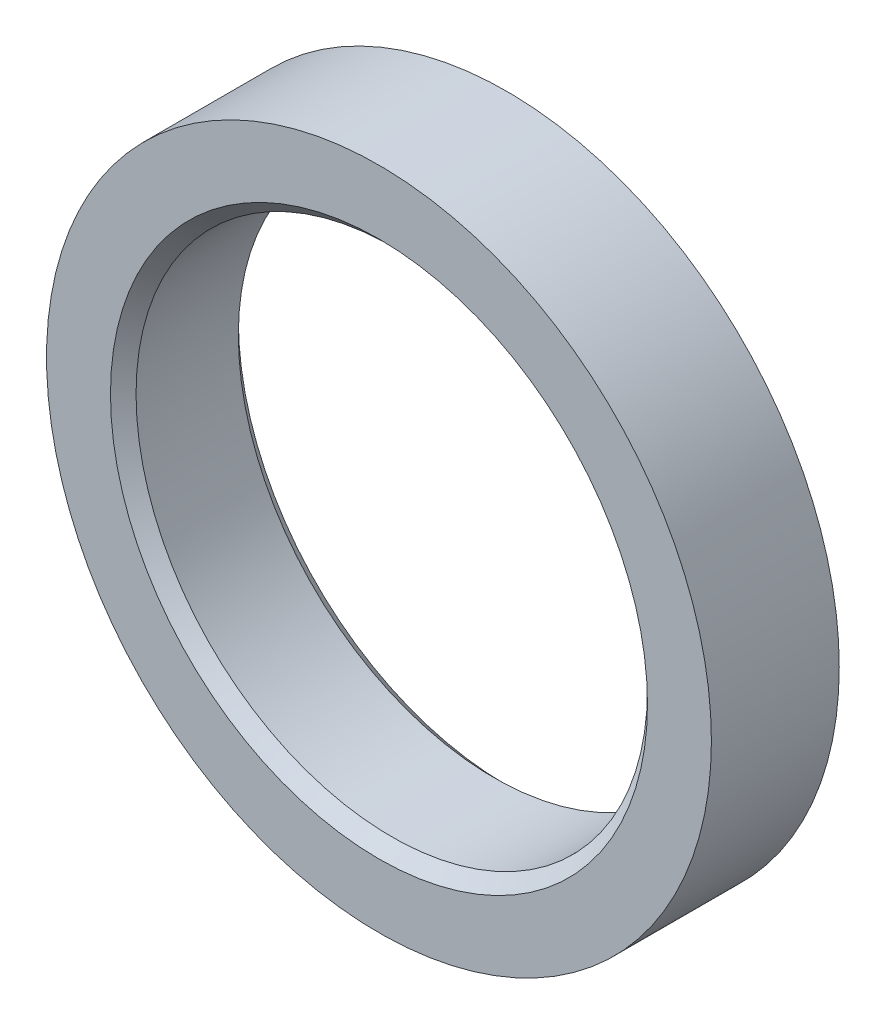
SolidWorks part; units mm, degrees
material "45"
ref_plane "前视基准面" through (0, 0, 0) normal (0, 0, 1) x (1, 0, 0)
ref_plane "上视基准面" through (0, 0, 0) normal (0, 1, 0) x (1, 0, 0)
ref_plane "右视基准面" through (0, 0, 0) normal (1, 0, 0) x (0, 0, -1)
sketch "草图1" plane through (0, 0, 0) normal (0, 0, 1) x (1, 0, 0)
  circle A0 centre (0, 0) radius 13
  circle A1 centre (0, 0) radius 10
  dimension "D1" = 20
  dimension "D2" = 26
extrude "凸台-拉伸1" add sketch "草图1" along normal blind 5
chamfer "倒角1" distance 0.5 angle 45 2 edges at (10, 0, 0) (10, 0, 5)
